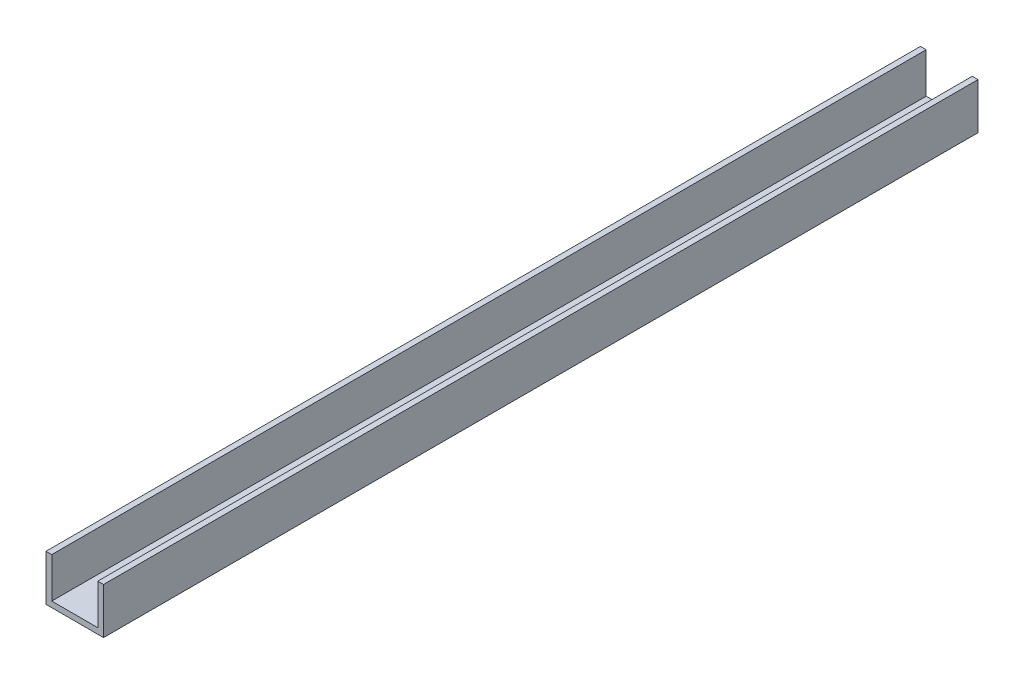
SolidWorks part; units mm, degrees
ref_plane "Front Plane" through (0, 0, 0) normal (0, 0, 1) x (1, 0, 0)
ref_plane "Top Plane" through (0, 0, 0) normal (0, 1, 0) x (1, 0, 0)
ref_plane "Right Plane" through (0, 0, 0) normal (1, 0, 0) x (0, 0, -1)
sketch "Sketch1" plane through (0, 0, 0) normal (0, 0, 1) x (1, 0, 0)
  line L0 (0, 0) -> (7.9375, 0)
  line L1 (7.9375, 0) -> (7.9375, 12.7)
  line L2 (7.9375, 12.7) -> (6.35, 12.7)
  line L3 (6.35, 12.7) -> (6.35, 1.5875)
  line L4 (6.35, 1.5875) -> (-6.35, 1.5875)
  line L5 (-6.35, 1.5875) -> (-6.35, 12.7)
  line L6 (-6.35, 12.7) -> (-7.9375, 12.7)
  line L7 (-7.9375, 12.7) -> (-7.9375, 0)
  line L8 (-7.9375, 0) -> (0, 0)
  line L9 (0, 0) -> (0, 1.5875) construction
  dimension "D1" = 15.875
  dimension "D2" = 12.7
  dimension "D3" = 1.5875
extrude "Boss-Extrude1" add sketch "Sketch1" along normal blind 241.3
